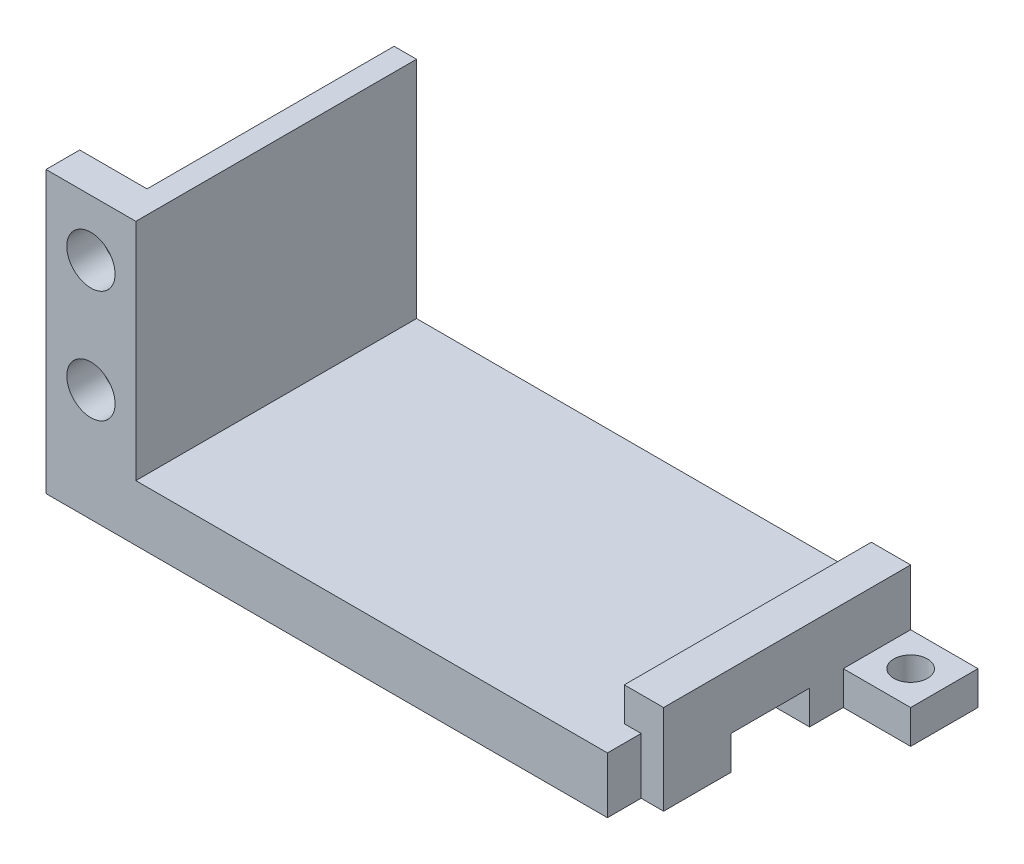
SolidWorks part; units mm, degrees
ref_plane "Alzado" through (0, 0, 0) normal (0, 0, 1) x (1, 0, 0)
ref_plane "Planta" through (0, 0, 0) normal (0, 1, 0) x (1, 0, 0)
ref_plane "Vista lateral" through (0, 0, 0) normal (1, 0, 0) x (0, 0, -1)
sketch "Croquis1" plane through (0, 0, 0) normal (0, 0, 1) x (1, 0, 0)
  line L1 (-3.3, 10) -> (3.3, 10)
  line L2 (-3.3, 10) -> (-3.3, -10)
  line L3 (-3.3, -10) -> (3.3, -10)
  line L4 (3.3, 10) -> (3.3, -10)
  line L5 (-3.3, 10) -> (3.3, -10) construction
  line L6 (-3.3, -10) -> (3.3, 10) construction
  point P0 (0, 0)
  dimension "D1" = 6.6
  dimension "D2" = 20
extrude "Saliente-Extruir1" add sketch "Croquis1" along normal blind 3
sketch "Croquis2" plane through (0, 0, 3) normal (0, 0, 1) x (1, 0, 0)
  line L0 (3.3, -10) -> (3.3, 10) construction
  line L1 (3.3, 10) -> (-3.3, 10) construction
  line L2 (-3.3, -10) -> (3.3, -10) construction
  circle A0 centre (-0.6, 5.85) radius 2.15
  circle A1 centre (-0.6, -5.85) radius 2.15
  dimension "D1" = 3.9
  dimension "D2" = 3.9
  dimension "D3" = 4.15
  dimension "D4" = 4.15
extrude "Cortar-Extruir1" cut sketch "Croquis2" against normal blind 3
sketch "Croquis3" plane through (0, 0, 0) normal (0, 0, -1) x (-1, 0, 0)
  line L1 (-3.3, 10) -> (-1.3, 10)
  line L2 (-3.3, 10) -> (-3.3, -10)
  line L3 (-3.3, -10) -> (-1.3, -10)
  line L4 (-1.3, 10) -> (-1.3, -10)
extrude "Saliente-Extruir3" add sketch "Croquis3" along normal blind 22
sketch "Croquis5" plane through (0, -10, 0) normal (0, -1, 0) x (-1, 0, 0)
  line L1 (-3.3, 22) -> (-45.3, 22)
  line L2 (-3.3, 22) -> (-3.3, -3)
  line L3 (-3.3, -3) -> (-45.3, -3)
  line L4 (-45.3, 22) -> (-45.3, -3)
  dimension "D1" = 42
extrude "Saliente-Extruir4" add sketch "Croquis5" along normal blind 5 separate body
sketch "Croquis6" plane through (0, -10, 0) normal (0, 1, 0) x (1, 0, 0)
  line L1 (45.3, 22) -> (47.3, 22)
  line L2 (45.3, 22) -> (45.3, 0)
  line L3 (45.3, 0) -> (47.3, 0)
  line L4 (47.3, 22) -> (47.3, 0)
extrude "Saliente-Extruir5" add sketch "Croquis6" along normal blind 3 separate body
sketch "Croquis7" plane through (0, -10, 0) normal (0, -1, 0) x (-1, 0, 0)
  line L0 (-3.3, -3) -> (-3.3, 22) construction
  line L1 (3.3, -3) -> (-3.3, -3)
  line L2 (3.3, -3) -> (3.3, 0)
  line L3 (3.3, 0) -> (-3.3, 0)
  line L4 (-3.3, -3) -> (-3.3, 0)
  line L6 (-47.3, 0) -> (-45.3, 0)
  line L7 (-47.3, 0) -> (-47.3, 22)
  line L8 (-47.3, 22) -> (-45.3, 22)
  line L9 (-45.3, 0) -> (-45.3, 22)
extrude "Saliente-Extruir6" add sketch "Croquis7" along normal blind 5
sketch "Croquis8" plane through (0, -10, 0) normal (0, -1, 0) x (-1, 0, 0)
  line L0 (-45.3, -3) -> (-3.3, -3) construction
  line L1 (-1.3, 22) -> (-12.462, 22)
  line L2 (-1.3, 22) -> (-1.3, -3)
  line L3 (-1.3, -3) -> (-12.462, -3)
  line L4 (-12.462, 22) -> (-12.462, -3)
extrude "Saliente-Extruir7" add sketch "Croquis8" along normal blind 5
sketch "Croquis9" plane through (1.3, 0, 0) normal (-1, 0, 0) x (0, 0, 1)
  line L1 (-22, -15) -> (-16, -15)
  line L2 (-22, -15) -> (-22, -12)
  line L3 (-22, -12) -> (-16, -12)
  line L4 (-16, -15) -> (-16, -12)
extrude "Saliente-Extruir8" add sketch "Croquis9" along normal blind 6
sketch "Croquis10" plane through (0, -12, 0) normal (0, 1, 0) x (1, 0, 0)
  line L0 (-4.7, 16) -> (-4.7, 22) construction
  line L1 (-4.7, 22) -> (1.3, 22) construction
  circle A0 centre (-1.7, 19) radius 1.5
  dimension "D1" = 3
  dimension "D2" = 3
extrude "Cortar-Extruir2" cut sketch "Croquis10" against normal blind 6
sketch "Croquis11" plane through (47.3, 0, 0) normal (1, 0, 0) x (0, 0, -1)
  line L1 (22, -15) -> (16, -15)
  line L2 (22, -15) -> (22, -12)
  line L3 (22, -12) -> (16, -12)
  line L4 (16, -15) -> (16, -12)
extrude "Saliente-Extruir9" add sketch "Croquis11" along normal blind 6
sketch "Croquis12" plane through (0, -12, 0) normal (0, 1, 0) x (1, 0, 0)
  line L0 (53.3, 22) -> (47.3, 22) construction
  line L1 (53.3, 22) -> (53.3, 16) construction
  circle A0 centre (50.3, 19) radius 1.5
  dimension "D1" = 3
  dimension "D2" = 3
extrude "Cortar-Extruir3" cut sketch "Croquis12" against normal blind 6
sketch "Croquis14" plane through (0, 0, 3) normal (0, 0, 1) x (1, 0, 0)
  line L0 (-3.3, 10) -> (-3.3, -15) construction
  line L1 (3.3, 10) -> (-3.3, 10)
  line L2 (3.3, 10) -> (3.3, -10.0222)
  line L3 (3.3, -10.0222) -> (-3.3, -10.0222)
  line L4 (-3.3, 10) -> (-3.3, -10.0222)
extrude "Saliente-Extruir10" add sketch "Croquis14" against normal blind 3
sketch "Croquis15" plane through (0, 0, 3) normal (0, 0, 1) x (1, 0, 0)
  line L0 (45.3, -10) -> (3.3, -10) construction
  line L1 (3.3, -10) -> (3.3, 10) construction
  circle A0 centre (-0.7, -5) radius 1.5
  circle A1 centre (-0.7, 5) radius 1.5
  dimension "D1" = 5
  dimension "D2" = 10
  dimension "D3" = 4
extrude "Cortar-Extruir4" cut sketch "Croquis15" against normal blind 28
sketch "Croquis16" plane through (0, 0, 3) normal (0, 0, 1) x (1, 0, 0)
  circle A0 centre (-0.7, -5) radius 2.15
  circle A1 centre (-0.7, 5) radius 2.15
extrude "Cortar-Extruir5" cut sketch "Croquis16" against normal blind 39.9623
sketch "Croquis18" plane through (-3.3, 0, 0) normal (-1, 0, 0) x (0, 0, 1)
  line L1 (3, 10) -> (0, 10)
  line L2 (3, 10) -> (3, -15)
  line L3 (3, -15) -> (0, -15)
  line L4 (0, 10) -> (0, -15)
extrude "Saliente-Extruir11" add sketch "Croquis18" along normal blind 1.4
sketch "Croquis19" plane through (0, -7, 0) normal (0, 1, 0) x (1, 0, 0)
  line L0 (45.3, 0) -> (47.3, 0) construction
  line L1 (47.3, 22) -> (43.8, 22)
  line L2 (47.3, 22) -> (47.3, 0)
  line L3 (47.3, 0) -> (43.8, 0)
  line L4 (43.8, 22) -> (43.8, 0)
  line L5 (45.3, 22) -> (45.3, 0) construction
  dimension "D1" = 0
  dimension "D2" = 1.5
extrude "Saliente-Extruir12" add sketch "Croquis19" against normal blind 7.4
sketch "Croquis21" plane through (1.3, 0, 0) normal (-1, 0, 0) x (0, 0, 1)
  line L0 (0, -15) -> (-16, -15) construction
  line L1 (-13, -15) -> (-6, -15)
  line L2 (-13, -15) -> (-13, -12)
  line L3 (-13, -12) -> (-6, -12)
  line L4 (-6, -15) -> (-6, -12)
  line L5 (-22, -12) -> (-22, -15) construction
  line L6 (3, -15) -> (3, 10) construction
  dimension "D1" = 9
  dimension "D2" = 9
  dimension "D3" = 3
extrude "Cortar-Extruir6" cut sketch "Croquis21" against normal blind 47
